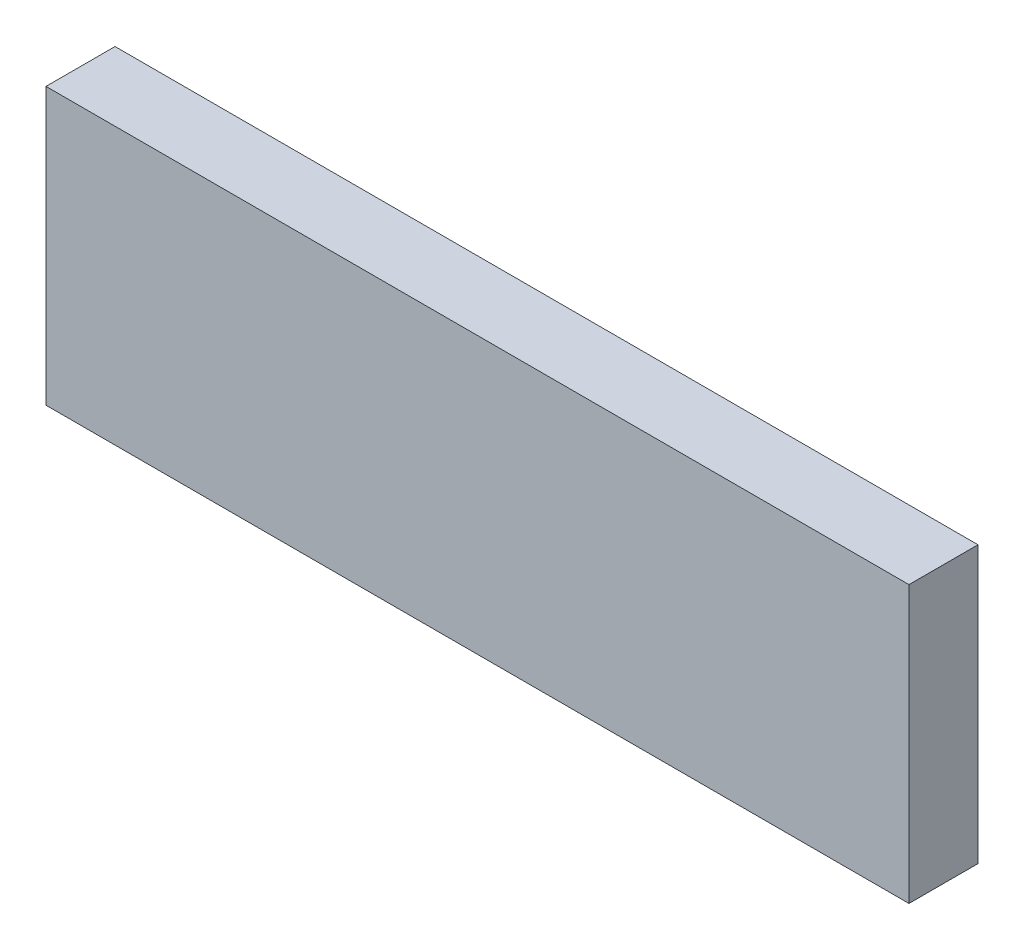
SolidWorks part; units mm, degrees
ref_plane "前视基准面" through (0, 0, 0) normal (0, 0, 1) x (1, 0, 0)
ref_plane "上视基准面" through (0, 0, 0) normal (0, 1, 0) x (1, 0, 0)
ref_plane "右视基准面" through (0, 0, 0) normal (1, 0, 0) x (0, 0, -1)
other "Configuration Table"
sketch "草图1" plane through (0, 0, 0) normal (0, 0, 1) x (1, 0, 0)
  line L1 (-125, -40) -> (125, -40)
  line L2 (-125, -40) -> (-125, 40)
  line L3 (-125, 40) -> (125, 40)
  line L4 (125, -40) -> (125, 40)
  line L5 (-125, -40) -> (125, 40) construction
  line L6 (-125, 40) -> (125, -40) construction
  point P0 (0, 0)
extrude "凸台-拉伸1" add sketch "草图1" along normal blind 20
